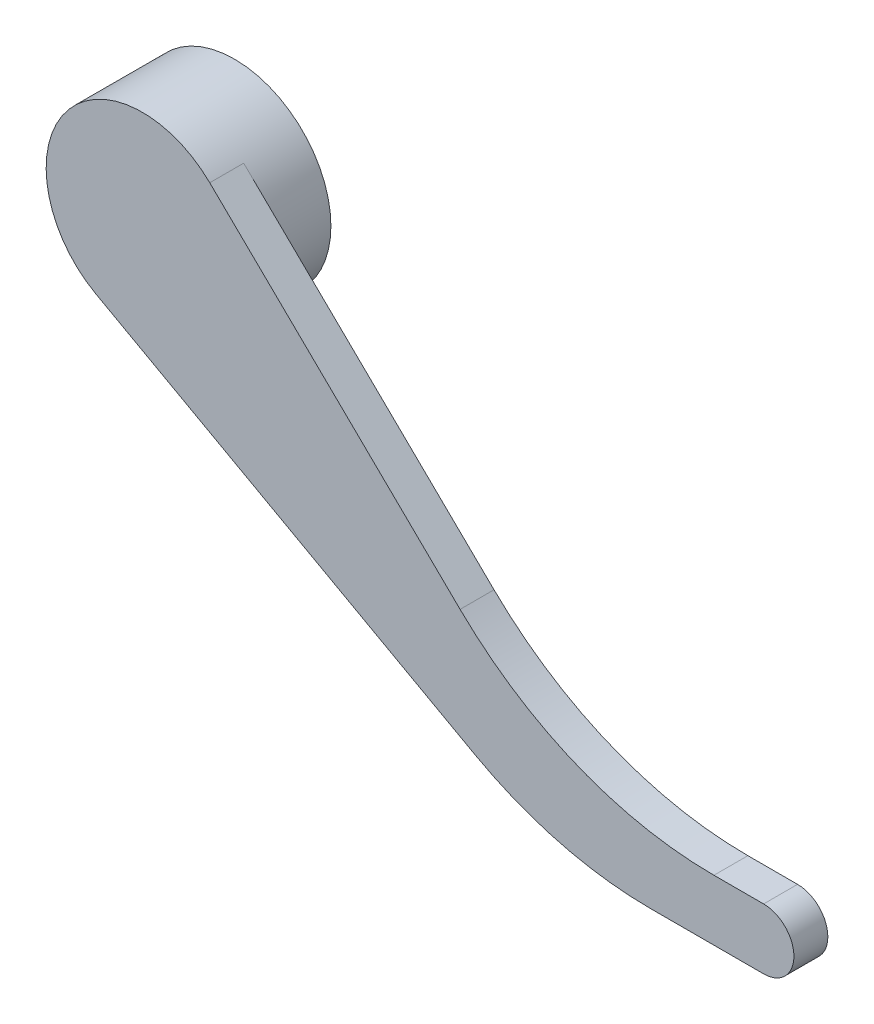
SolidWorks part; units mm, degrees
ref_plane "Front Plane" through (0, 0, 0) normal (0, 0, 1) x (1, 0, 0)
ref_plane "Top Plane" through (0, 0, 0) normal (0, 1, 0) x (1, 0, 0)
ref_plane "Right Plane" through (0, 0, 0) normal (1, 0, 0) x (0, 0, -1)
sketch "Sketch1" plane through (0, 0, 0) normal (0, 0, 1) x (1, 0, 0)
  line L0 (0, 0) -> (0, -5) construction
  line L1 (0, 0) -> (12, 0) construction
  line L2 (0, 0) -> (0, 12) construction
  line L3 (0, 12) -> (12, 12) construction
  line L4 (12, 0) -> (12, 12) construction
  line L5 (6, 6) -> (6, -21) construction
  line L6 (0, 12) -> (12, 0) construction
  line L7 (12, 12) -> (0, 0) construction
  line L8 (0, -5) -> (26, -5) construction
  line L9 (26, -48.5374) -> (26, 38.5374) construction
  line L10 (6, 6) -> (13, 6) construction
  line L11 (13, -21) -> (6, 6) construction
  line L12 (-14, -21) -> (26, -21) construction
  line L13 (12, 0) -> (26, 0) construction
  line L14 (6, 6) -> (31.632, -5) construction
  line L15 (19.1064, -1.2356) -> (8.7761, 8.8449)
  line L16 (29.5824, -5.5) -> (31.632, -5.5)
  line L17 (31.632, -5.5) -> (31.632, -8) construction
  line L18 (31.632, -8) -> (26.9881, -8)
  line L20 (19.7343, -6.1294) -> (4.0777, 2.5207)
  arc A2 (31.632, -8) -> (31.632, -5.5) centre (31.632, -6.75) ccw
  circle A3 centre (6, 6) radius 3.975 construction
  arc A4 (4.0777, 2.5207) -> (8.7761, 8.8449) centre (6, 6) cw
  arc A5 (26.9881, -8) -> (19.7343, -6.1294) centre (26.9881, 7) cw
  arc A6 (19.1064, -1.2356) -> (29.5824, -5.5) centre (29.5824, 9.5) ccw
  point P6 (6, 6)
  point P14 (26, -5)
  point P18 (6, -21)
  dimension "D10" = 15
  dimension "D11" = 7.95
  dimension "D1" = 12
  dimension "D2" = 5
  dimension "D3" = 26
  dimension "D4" = 16
  dimension "D5" = 27
  dimension "D6" = 7
  dimension "D7" = 27.8927
  dimension "D8" = 2.5
  dimension "D9" = 1
extrude "Boss-Extrude1" add sketch "Sketch1" along normal blind 1.4
sketch "Sketch2" plane through (0, 0, 1.4) normal (0, 0, 1) x (1, 0, 0)
  circle A0 centre (6, 6) radius 3.975
  circle A1 centre (6, 6) radius 2.475
  arc A3 (8.7761, 8.8449) -> (4.0777, 2.5207) centre (6, 6) ccw construction
  dimension "D1" = 4.95
extrude "Boss-Extrude2" add sketch "Sketch2" against normal blind 3.8
sketch "Sketch3" plane through (0, 0, 0) normal (0, 0, -1) x (-1, 0, 0)
  line L0 (-6, 6) -> (-5.5947, 8.4416) construction
  line L1 (-5.6111, 8.3429) -> (-5.4983, 8.4236)
  line L2 (-5.4983, 8.4236) -> (-5.6111, 8.3429)
  line L3 (-5.6918, 8.4557) -> (-5.6111, 8.3429)
  line L4 (-5.6918, 8.4557) -> (-5.4983, 8.4236) construction
  line L5 (-5.6918, 8.4557) -> (-5.6882, 8.4776)
  line L6 (-5.4983, 8.4236) -> (-5.4947, 8.4455)
  line L7 (-5.6882, 8.4776) -> (-5.4947, 8.4455)
  circle A1 centre (-6, 6) radius 2.375 construction
  circle A3 centre (-6, 6) radius 2.475 construction
  circle A4 centre (-6, 6) radius 2.475 construction
  point P6 (-5.6111, 8.3429)
  circle M5 centre (-6, 6) radius 2.475
  dimension "D1" = 0.1
extrude "Boss-Extrude4" add sketch "Sketch3" along normal up to surface (2.4 mm away) contours L3 L1 M5
pattern_circular "CirPattern1" count 60 over 360 about axis through (6.0002, 5.9988, 0) along (0, 0, 1) of "Boss-Extrude4"
